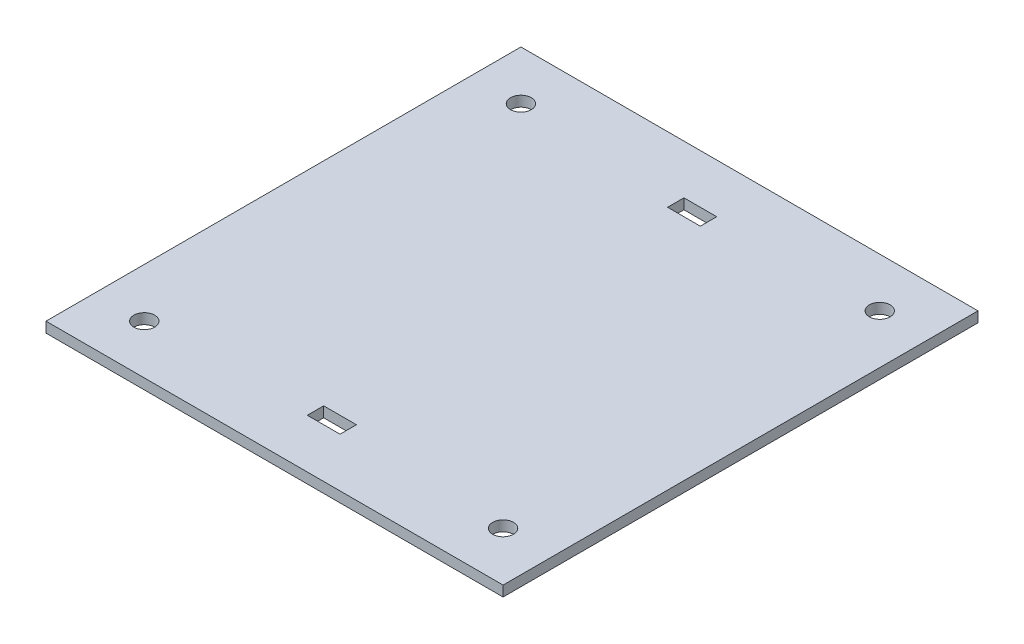
SolidWorks part; units mm, degrees
material "Acrylic (Medium-high impact)"
ref_plane "Front Plane" through (0, 0, 0) normal (0, 0, 1) x (1, 0, 0)
ref_plane "Top Plane" through (0, 0, 0) normal (0, 1, 0) x (1, 0, 0)
ref_plane "Right Plane" through (0, 0, 0) normal (1, 0, 0) x (0, 0, -1)
sketch "Sketch1" plane through (0, 0, 0) normal (0, 1, 0) x (1, 0, 0)
  line L0 (69.775, 145) -> (69.775, 0) construction
  line L1 (0, 0) -> (139.55, 0)
  line L2 (0, 0) -> (0, 145)
  line L3 (0, 145) -> (139.55, 145)
  line L4 (139.55, 0) -> (139.55, 145)
  line L5 (0, 72.5) -> (139.55, 72.5) construction
  line L6 (64.775, 130) -> (74.775, 130)
  line L7 (64.775, 130) -> (64.775, 125)
  line L8 (64.775, 125) -> (74.775, 125)
  line L9 (74.775, 130) -> (74.775, 125)
  line L10 (64.775, 15) -> (64.775, 20)
  line L11 (64.775, 20) -> (74.775, 20)
  line L12 (74.775, 15) -> (74.775, 20)
  line L13 (64.775, 15) -> (74.775, 15)
  circle A0 centre (15, 130) radius 3.175
  circle A1 centre (124.55, 130) radius 3.175
  circle A2 centre (15, 15) radius 3.175
  circle A3 centre (124.55, 15) radius 3.175
  point P11 (69.775, 130)
  point P14 (64.775, 127.5)
  point P15 (64.775, 17.5)
  dimension "D7" = 6.35
  dimension "D1" = 139.55
  dimension "D2" = 145
  dimension "D3" = 15
  dimension "D4" = 10
  dimension "D5" = 5
  dimension "D6" = 0
  dimension "D8" = 15
  dimension "D9" = 15
extrude "Boss-Extrude2" add sketch "Sketch1" along normal blind 3.175 contours L4 L3 L2 L1 | L6 L9 L8 L7 | A1 | A3 | L13 L12 L11 L10 | A2 | A0
